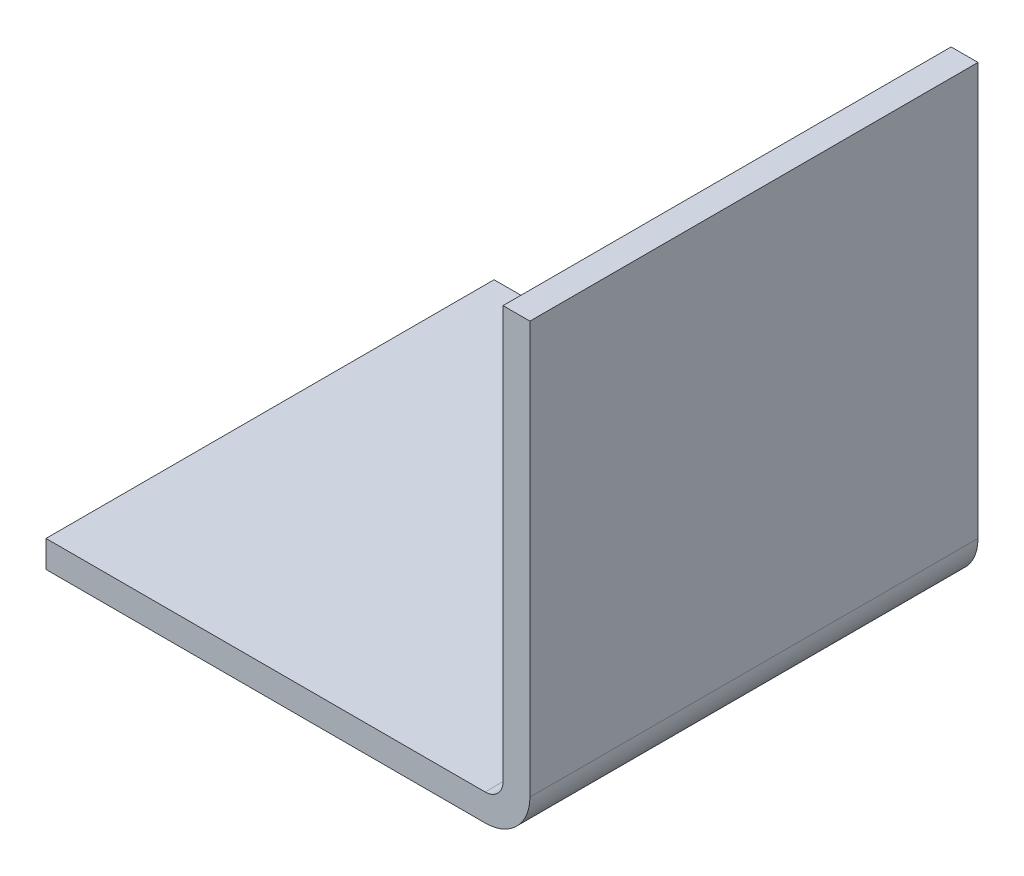
SolidWorks part; units mm, degrees
ref_plane "Front Plane" through (0, 0, 0) normal (0, 0, 1) x (1, 0, 0)
ref_plane "Top Plane" through (0, 0, 0) normal (0, 1, 0) x (1, 0, 0)
ref_plane "Right Plane" through (0, 0, 0) normal (1, 0, 0) x (0, 0, -1)
sketch "Sketch1" plane through (0, 0, 0) normal (0, 0, 1) x (1, 0, 0)
  line L0 (0, 51) -> (0, 5)
  line L1 (-5, 0) -> (-54, 0)
  arc A0 (0, 5) -> (-5, 0) centre (-5, 5) cw
  point P3 (0, 0)
  point P7 (0, 0)
  dimension "D3" = 5
  dimension "D1" = 54
  dimension "D2" = 51
extrude "Extrude-Thin1" add sketch "Sketch1" along normal blind 50 thin
